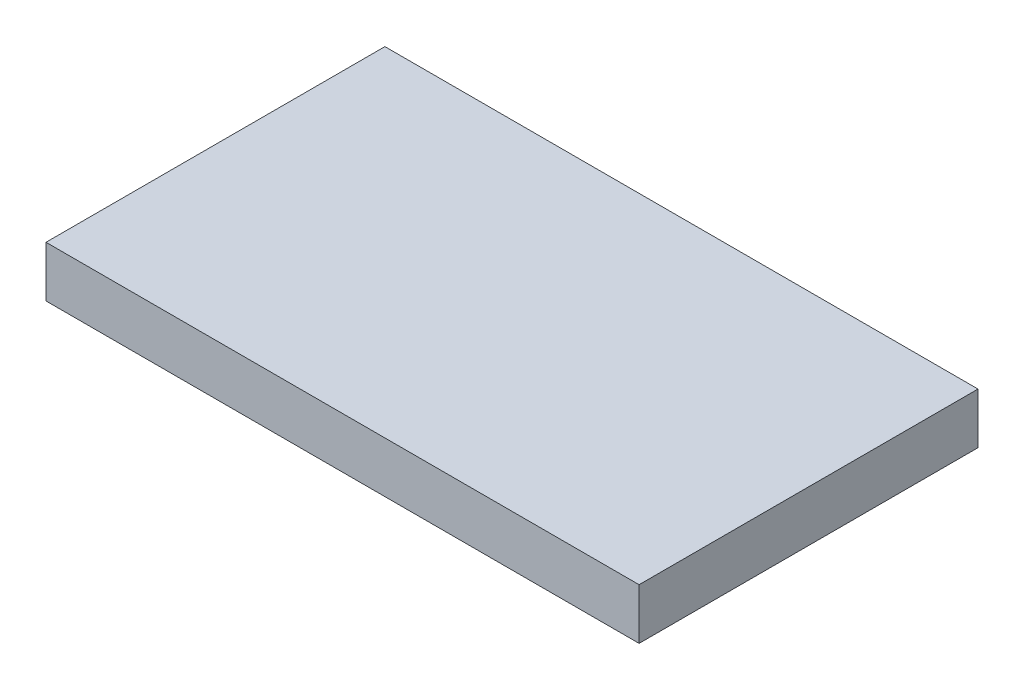
SolidWorks part; units mm, degrees
ref_plane "Front Plane" through (0, 0, 0) normal (0, 0, 1) x (1, 0, 0)
ref_plane "Top Plane" through (0, 0, 0) normal (0, 1, 0) x (1, 0, 0)
ref_plane "Right Plane" through (0, 0, 0) normal (1, 0, 0) x (0, 0, -1)
sketch "Sketch1" plane through (0, 0, 0) normal (0, 1, 0) x (1, 0, 0)
  line L1 (-8.75, 5) -> (8.75, 5)
  line L2 (-8.75, 5) -> (-8.75, -5)
  line L3 (-8.75, -5) -> (8.75, -5)
  line L4 (8.75, 5) -> (8.75, -5)
  line L5 (-8.75, 5) -> (8.75, -5) construction
  line L6 (-8.75, -5) -> (8.75, 5) construction
  point P0 (0, 0)
  dimension "D1" = 17.5
  dimension "D2" = 10
extrude "Boss-Extrude1" add sketch "Sketch1" along normal blind 1.5 contours L1 L4 L3 L2
